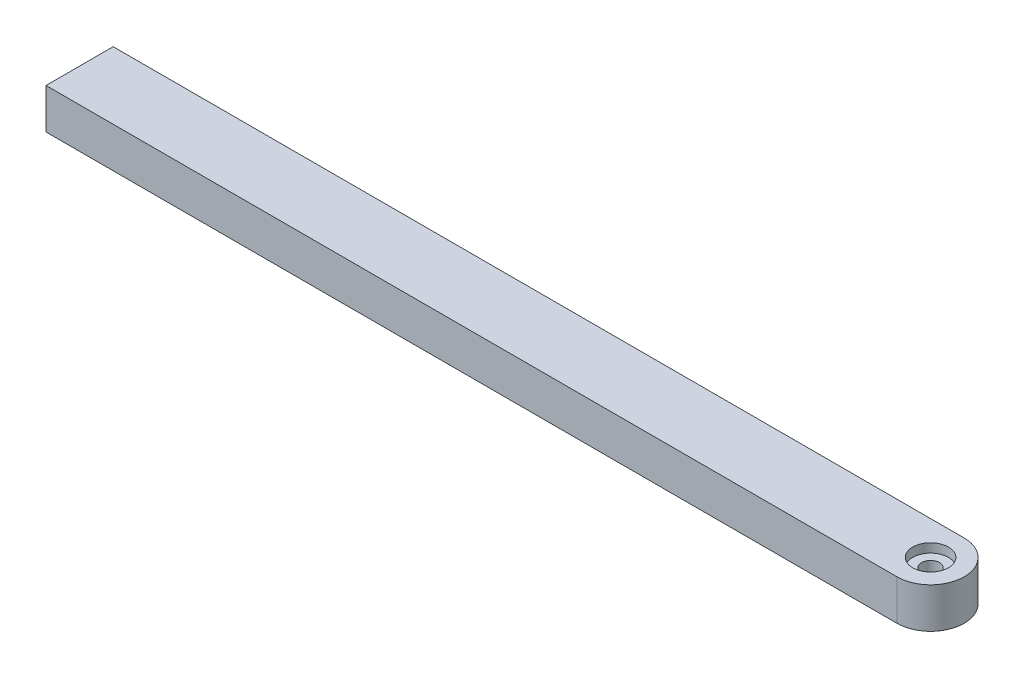
SolidWorks part; units mm, degrees
ref_plane "Front Plane" through (0, 0, 0) normal (0, 0, 1) x (1, 0, 0)
ref_plane "Top Plane" through (0, 0, 0) normal (0, 1, 0) x (1, 0, 0)
ref_plane "Right Plane" through (0, 0, 0) normal (1, 0, 0) x (0, 0, -1)
sketch "Sketch1" plane through (0, 0, 0) normal (0, 1, 0) x (1, 0, 0)
  line L0 (200, 0) -> (180, 0) construction
  line L2 (-200, 15) -> (-200, -15)
  line L5 (0, -15) -> (0, 15) construction
  line L6 (-200, 0) -> (200, 0) construction
  line L7 (-200, 15) -> (180, 15)
  line L8 (-200, -15) -> (180, -15)
  circle A0 centre (180, 0) radius 4
  arc A1 (180, 15) -> (180, -15) centre (180, 0) cw
  point P0 (0, 0)
  point P1 (0, 0)
  point P8 (0, 0)
  dimension "D4" = 8
  dimension "D1" = 30
  dimension "D3" = 20
extrude "Boss-Extrude1" add sketch "Sketch1" along normal blind 18
sketch "Sketch2" plane through (0, 18, 0) normal (0, 1, 0) x (1, 0, 0)
  circle A0 centre (180, 0) radius 8
  dimension "D1" = 16
extrude "Cut-Extrude1" cut sketch "Sketch2" against normal blind 4
